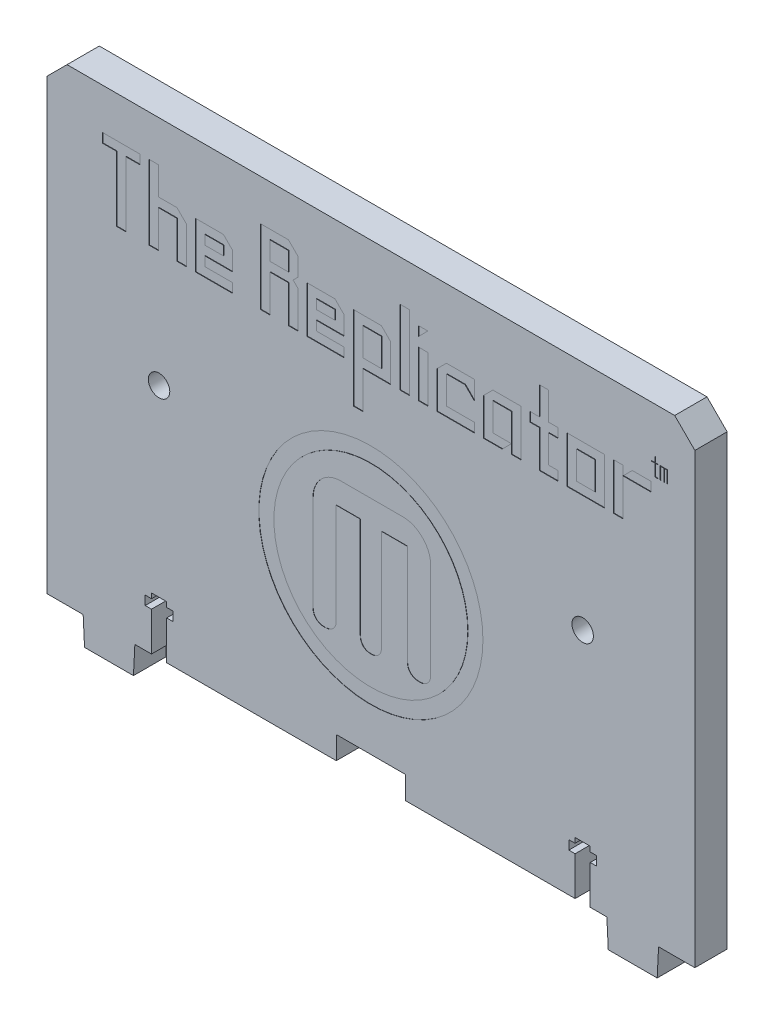
SolidWorks part; units mm, degrees
ref_plane "Front Plane" through (0, 0, 0) normal (0, 0, 1) x (1, 0, 0)
ref_plane "Top Plane" through (0, 0, 0) normal (0, 1, 0) x (1, 0, 0)
ref_plane "Right Plane" through (0, 0, 0) normal (1, 0, 0) x (0, 0, -1)
sketch "Sketch1" plane through (0, 0, 0) normal (0, 0, 1) x (1, 0, 0)
  line L0 (-37.2336, 42.2153) -> (-37.2336, -46.6247)
  line L1 (87.2664, 46.2153) -> (-33.2336, 46.2153)
  line L2 (91.2664, 42.2153) -> (91.2664, -46.6247)
  line L3 (91.2664, -46.6247) -> (84.0664, -46.6247)
  line L4 (-37.2336, -46.6247) -> (-30.0336, -46.6247)
  line L5 (-37.2336, 42.2153) -> (-33.2336, 46.2153)
  line L7 (91.2664, 42.2153) -> (87.2664, 46.2153)
  line L8 (33.8664, -46.6247) -> (33.8664, -42.1247)
  line L9 (-29.7586, -52.1247) -> (-20.0586, -52.1247)
  line L10 (-29.7586, -52.1247) -> (-30.0336, -46.6247)
  line L11 (-20.0586, -52.1247) -> (-19.7836, -46.6247)
  line L13 (20.1664, -46.6247) -> (20.1664, -42.1247)
  line L89 (33.8664, -42.1247) -> (20.1664, -42.1247)
  line L125 (83.7914, -52.1247) -> (84.0664, -46.6247)
  line L126 (-12.2336, -37.1247) -> (-13.4823, -37.1247)
  line L127 (70.5164, -37.1247) -> (71.7664, -37.1247)
  line L128 (66.2664, -38.9247) -> (67.515, -38.9247)
  line L129 (-17.7336, -37.1247) -> (-17.7336, -38.9247)
  line L130 (70.5164, -36.1247) -> (70.5164, -37.1247)
  line L131 (71.7664, -37.1247) -> (71.7664, -38.9247)
  line L132 (-12.2336, -38.9247) -> (-13.4823, -38.9247)
  line L133 (-13.4823, -38.9247) -> (-13.4823, -46.6247)
  line L134 (-16.4836, -37.1247) -> (-17.7336, -37.1247)
  line L135 (66.2664, -37.1247) -> (67.515, -37.1247)
  line L137 (-16.4836, -36.1247) -> (-13.4823, -36.1247)
  line L138 (67.515, -38.9247) -> (67.515, -46.6247)
  line L139 (70.5164, -38.9247) -> (70.5164, -46.6247)
  line L140 (-17.7336, -38.9247) -> (-16.4836, -38.9247)
  line L141 (74.0914, -52.1247) -> (83.7914, -52.1247)
  line L142 (-13.4823, -36.1247) -> (-13.4823, -37.1247)
  line L143 (66.2664, -37.1247) -> (66.2664, -38.9247)
  line L145 (-12.2336, -37.1247) -> (-12.2336, -38.9247)
  line L146 (74.0914, -52.1247) -> (73.8164, -46.6247)
  line L147 (71.7664, -38.9247) -> (70.5164, -38.9247)
  line L148 (-16.4836, -38.9247) -> (-16.4836, -46.6247)
  line L149 (67.515, -36.1247) -> (67.515, -37.1247)
  line L150 (-16.4836, -36.1247) -> (-16.4836, -37.1247)
  line L151 (70.5164, -36.1247) -> (67.515, -36.1247)
  line L152 (-13.4823, -46.6247) -> (20.1664, -46.6247)
  line L153 (-19.7836, -46.6247) -> (-16.4836, -46.6247)
  line L154 (67.515, -46.6247) -> (33.8664, -46.6247)
  line L155 (73.8164, -46.6247) -> (70.5164, -46.6247)
  circle A0 centre (-14.983, 0.2416) radius 2.125
  circle A1 centre (69.0157, 0.2416) radius 2.125
  point P93 (27.0164, -40.5247)
  dimension "D3" = 4.25
extrude "Boss-Extrude1" add sketch "Sketch1" along normal blind 6.4
sketch "Sketch2" plane through (0, 0, 6.4) normal (0, 0, 1) x (1, 0, 0)
  line L0 (34.2644, -22.6031) -> (34.2644, -2.7541)
  line L1 (38.8838, -22.5844) -> (38.8838, -3.7647)
  line L2 (33.248, 1.8654) -> (21.1687, 1.8654)
  line L3 (15.5328, -3.7647) -> (15.5328, -22.5853)
  line L4 (20.1523, -22.6021) -> (20.1523, -2.7541)
  line L5 (20.1523, -2.7541) -> (24.8986, -2.7541)
  line L6 (24.8986, -2.7541) -> (24.8986, -22.6)
  line L7 (29.1434, -22.6) -> (29.1434, -2.7541)
  line L8 (29.1434, -2.7541) -> (34.2644, -2.7541)
  circle A0 centre (27.0136, -11.3473) radius 19.2258
  circle A1 centre (27.0136, -11.3473) radius 22.2258
  spline S0 degree 3 poles (34.2644, -22.6031) (34.2698, -22.7578) (34.2746, -22.913) (34.3187, -23.2193) (34.3612, -23.3661) (34.4711, -23.6521) (34.5384, -23.7926) (34.7062, -24.0461) (34.8074, -24.1612) (35.1475, -24.4744) (35.4177, -24.6332) (35.8518, -24.7756) (36.0034, -24.8079) (36.3084, -24.8442) (36.4619, -24.8505) (36.6155, -24.8569) knots 0 0 0 0 0.125 0.125 0.25 0.25 0.375 0.375 0.5 0.5 0.75 0.75 0.875 0.875 1 1 1 1
  spline S1 degree 3 poles (36.6155, -24.8569) (36.767, -24.8508) (36.9189, -24.8449) (37.2193, -24.8054) (37.3648, -24.7698) (37.6463, -24.6664) (37.7834, -24.5977) (38.0348, -24.4343) (38.1507, -24.3391) (38.4709, -24.0157) (38.6328, -23.7538) (38.7905, -23.3328) (38.8305, -23.1857) (38.8724, -22.8865) (38.8778, -22.7354) (38.8838, -22.5844) knots 0 0 0 0 0.125 0.125 0.25 0.25 0.375 0.375 0.5 0.5 0.75 0.75 0.875 0.875 1 1 1 1
  spline S2 degree 3 poles (38.8838, -3.7647) (38.8784, -3.5782) (38.8731, -3.3917) (38.8439, -3.0196) (38.8194, -2.8353) (38.7173, -2.2917) (38.6129, -1.9393) (38.3325, -1.2544) (38.1569, -0.9229) (37.7384, -0.3186) (37.5005, -0.0366) (36.9765, 0.4911) (36.695, 0.7314) (36.0826, 1.1521) (35.7557, 1.3266) (35.0766, 1.6037) (34.7183, 1.7068) (33.9886, 1.8373) (33.6187, 1.8548) (33.248, 1.8654) knots 0 0 0 0 0.0625 0.0625 0.125 0.125 0.25 0.25 0.375 0.375 0.5 0.5 0.625 0.625 0.75 0.75 0.875 0.875 1 1 1 1
  spline S3 degree 3 poles (21.1687, 1.8654) (20.9822, 1.8601) (20.7957, 1.8549) (20.4237, 1.827) (20.2385, 1.8034) (19.6928, 1.7055) (19.3401, 1.6018) (18.6557, 1.3214) (18.3235, 1.146) (17.7187, 0.7283) (17.4383, 0.4895) (16.9144, -0.0386) (16.6751, -0.322) (16.2529, -0.9341) (16.081, -1.2613) (15.8038, -1.9399) (15.6979, -2.2966) (15.5961, -2.8428) (15.5721, -3.026) (15.5435, -3.3944) (15.5382, -3.5795) (15.5328, -3.7647) knots 0 0 0 0 0.0625 0.0625 0.125 0.125 0.25 0.25 0.375 0.375 0.5 0.5 0.625 0.625 0.75 0.75 0.875 0.875 0.9375 0.9375 1 1 1 1
  spline S4 degree 3 poles (15.5328, -22.5853) (15.5384, -22.7376) (15.5434, -22.8903) (15.5837, -23.1922) (15.6222, -23.3379) (15.7239, -23.622) (15.7863, -23.7622) (15.9426, -24.018) (16.0376, -24.1341) (16.2538, -24.3481) (16.3715, -24.4427) (16.6298, -24.6022) (16.7673, -24.6658) (17.0501, -24.7675) (17.1982, -24.8054) (17.4981, -24.8455) (17.6495, -24.8511) (17.8008, -24.8569) knots 0 0 0 0 0.125 0.125 0.25 0.25 0.375 0.375 0.5 0.5 0.625 0.625 0.75 0.75 0.875 0.875 1 1 1 1
  spline S5 degree 3 poles (17.8008, -24.8569) (17.9545, -24.8505) (18.1083, -24.8442) (18.4136, -24.8079) (18.5655, -24.7755) (19.0001, -24.6327) (19.2709, -24.474) (19.7238, -24.0546) (19.8981, -23.7942) (20.0608, -23.3654) (20.099, -23.2175) (20.1406, -22.9109) (20.1462, -22.7564) (20.1523, -22.6021) knots 0 0 0 0 0.125 0.125 0.25 0.25 0.5 0.5 0.75 0.75 0.875 0.875 1 1 1 1
  spline S6 degree 3 poles (24.8986, -22.6) (24.9126, -22.8932) (24.9308, -23.1889) (25.0582, -23.6064) (25.1172, -23.7426) (25.2586, -23.9976) (25.3397, -24.1184) (25.632, -24.4491) (25.8847, -24.6157) (26.2929, -24.77) (26.4363, -24.8054) (26.7275, -24.8444) (26.8743, -24.8506) (27.0211, -24.8568) knots 0 0 0 0 0.25 0.25 0.375 0.375 0.5 0.5 0.75 0.75 0.875 0.875 1 1 1 1
  spline S7 degree 3 poles (27.0211, -24.8568) (27.168, -24.8506) (27.3149, -24.8445) (27.6066, -24.8052) (27.7486, -24.7699) (28.1575, -24.6161) (28.4047, -24.4464) (28.7964, -24.008) (28.941, -23.7464) (29.0683, -23.329) (29.0965, -23.1838) (29.1296, -22.8929) (29.1365, -22.7465) (29.1434, -22.6) knots 0 0 0 0 0.125 0.125 0.25 0.25 0.5 0.5 0.75 0.75 0.875 0.875 1 1 1 1
extrude "Cut-Extrude1" cut sketch "Sketch2" against normal blind 0.05 contours S6 S7 L7 L8 L0 S0 S1 L1 S2 L2 S3 L3 S4 S5 L4 L5 L6 | A1 A0
sketch "Sketch3" plane through (0, 0, 6.4) normal (0, 0, 1) x (1, 0, 0)
  line L0 (83.4396, 37.2676) -> (83.4396, 36.2011)
  line L1 (83.4396, 33.8131) -> (83.9092, 33.8131)
  line L2 (82.7152, 36.2011) -> (83.3122, 36.2011)
  line L3 (84.3787, 33.6857) -> (84.3787, 36.2011)
  line L4 (84.3787, 36.2011) -> (85.1031, 36.2011)
  line L5 (85.2306, 36.0736) -> (85.2306, 33.6857)
  line L6 (85.1031, 36.2011) -> (85.8275, 36.2011)
  line L7 (85.8275, 36.2011) -> (85.8275, 33.6857)
  line L8 (83.3122, 37.2676) -> (83.4396, 37.2676)
  line L9 (82.7152, 36.2011) -> (82.7152, 36.0736)
  line L10 (83.9092, 36.2011) -> (83.9092, 36.0736)
  line L11 (83.9092, 33.8131) -> (83.9092, 33.6857)
  line L12 (84.3787, 33.6857) -> (84.5061, 33.6857)
  line L13 (85.1031, 33.6857) -> (85.2306, 33.6857)
  line L14 (85.7001, 33.6857) -> (85.8275, 33.6857)
  line L15 (83.4396, 36.0736) -> (83.4396, 33.8131)
  line L17 (83.4396, 36.2011) -> (83.9092, 36.2011)
  line L19 (83.4396, 36.0736) -> (83.9092, 36.0736)
  line L21 (83.3122, 36.0736) -> (83.3122, 33.6857)
  line L23 (53.0578, 23.3473) -> (54.9004, 25.1881)
  line L25 (78.8534, 32.56) -> (77.0109, 30.7177)
  line L159 (5.1518, 38.0876) -> (5.1518, 23.3473)
  line L160 (5.1518, 23.3473) -> (6.9943, 23.3473)
  line L161 (10.6794, 23.3473) -> (12.5219, 23.3473)
  line L162 (12.5219, 36.2451) -> (10.6794, 38.0876)
  line L163 (10.6794, 36.2451) -> (6.9943, 36.2451)
  line L164 (10.6794, 38.0876) -> (5.1518, 38.0876)
  line L165 (23.5772, 30.7175) -> (23.5772, 15.9771)
  line L166 (23.5772, 15.9771) -> (25.4197, 15.9771)
  line L167 (25.4197, 15.9771) -> (25.4197, 23.3473)
  line L168 (25.4197, 23.3473) -> (30.9473, 23.3473)
  line L169 (32.7899, 23.3473) -> (32.7899, 38.0876)
  line L170 (32.7899, 38.0876) -> (34.6324, 38.0876)
  line L171 (34.6324, 38.0876) -> (34.6324, 23.3473)
  line L172 (34.6324, 23.3473) -> (32.7899, 23.3473)
  line L173 (38.3175, 23.3473) -> (36.475, 23.3473)
  line L174 (40.16, 23.3473) -> (47.5302, 23.3473)
  line L175 (47.5302, 23.3473) -> (47.5302, 25.1898)
  line L176 (47.5302, 25.1898) -> (42.0026, 25.1898)
  line L177 (25.4197, 28.8749) -> (25.4197, 25.1898)
  line L178 (25.4197, 25.1898) -> (27.2623, 25.1898)
  line L179 (29.1048, 28.8749) -> (29.1048, 25.1898)
  line L180 (27.2623, 25.1898) -> (29.1048, 25.1898)
  line L181 (56.7429, 30.7175) -> (56.7429, 23.3473)
  line L182 (56.7429, 23.3473) -> (54.9004, 23.3473)
  line L183 (54.9004, 23.3473) -> (54.9004, 25.1881)
  line L185 (53.0578, 23.3473) -> (49.3727, 23.3473)
  line L186 (49.3727, 23.3473) -> (49.3727, 27.0324)
  line L187 (60.428, 23.3473) -> (62.2705, 23.3473)
  line L188 (62.2705, 38.0876) -> (60.428, 38.0876)
  line L189 (65.9556, 30.7175) -> (65.9556, 23.3473)
  line L190 (65.9556, 23.3473) -> (73.3258, 23.3473)
  line L191 (73.3258, 23.3473) -> (73.3258, 30.7175)
  line L192 (67.7982, 25.1898) -> (67.7982, 28.8749)
  line L193 (71.4832, 28.8749) -> (71.4832, 25.1898)
  line L194 (71.4832, 25.1898) -> (67.7982, 25.1898)
  line L195 (49.3727, 28.8749) -> (49.3727, 27.0324)
  line L196 (51.2153, 25.1898) -> (51.2153, 28.8749)
  line L197 (52.2946, 25.1898) -> (51.2153, 25.1898)
  line L198 (30.9473, 23.3473) -> (30.9473, 28.8749)
  line L199 (52.2946, 25.1898) -> (54.9004, 25.1898)
  line L200 (54.9004, 25.1898) -> (54.9004, 28.8749)
  line L201 (10.6794, 36.2451) -> (10.6794, 32.56)
  line L202 (6.9943, 32.56) -> (6.9943, 36.2451)
  line L203 (21.7346, 27.0324) -> (16.207, 27.0324)
  line L204 (16.207, 25.1898) -> (21.7346, 25.1898)
  line L205 (19.8921, 32.56) -> (21.7346, 30.7175)
  line L206 (21.7346, 30.7175) -> (21.7346, 27.0324)
  line L207 (18.0495, 28.8749) -> (19.8921, 28.8749)
  line L208 (19.8921, 28.8749) -> (19.8921, 30.7175)
  line L209 (19.8921, 30.7175) -> (16.207, 30.7175)
  line L210 (19.8921, 23.3473) -> (16.207, 23.3473)
  line L211 (21.7346, 25.1898) -> (21.7346, 23.3473)
  line L212 (21.7346, 23.3473) -> (19.8921, 23.3473)
  line L213 (30.9473, 28.8749) -> (30.9473, 30.7175)
  line L214 (30.9473, 30.7175) -> (29.1048, 32.56)
  line L215 (29.1048, 32.56) -> (23.5772, 32.56)
  line L216 (23.5772, 32.56) -> (23.5772, 30.7175)
  line L217 (25.4197, 28.8749) -> (25.4197, 30.7175)
  line L218 (25.4197, 30.7175) -> (29.1048, 30.7175)
  line L219 (29.1048, 30.7175) -> (29.1048, 28.8749)
  line L220 (36.475, 36.2451) -> (38.3175, 36.2451)
  line L221 (38.3175, 36.2451) -> (36.475, 34.4025)
  line L222 (36.475, 34.4025) -> (36.475, 36.2451)
  line L223 (36.475, 32.56) -> (38.3175, 32.56)
  line L224 (38.3175, 32.56) -> (38.3175, 23.3473)
  line L225 (36.475, 23.3473) -> (36.475, 32.56)
  line L226 (42.0026, 30.7175) -> (45.6877, 30.7175)
  line L227 (45.6877, 30.7175) -> (47.5302, 28.8749)
  line L228 (47.5302, 28.8749) -> (47.5302, 32.56)
  line L229 (42.0026, 25.1898) -> (42.0026, 30.7175)
  line L230 (56.7429, 30.7175) -> (56.7429, 32.56)
  line L231 (56.7429, 32.56) -> (51.2153, 32.56)
  line L232 (51.2153, 32.56) -> (49.3727, 30.7175)
  line L233 (49.3727, 30.7175) -> (49.3727, 28.8749)
  line L234 (51.2153, 28.8749) -> (51.2153, 30.7175)
  line L235 (51.2153, 30.7175) -> (54.9004, 30.7175)
  line L236 (54.9004, 30.7175) -> (54.9004, 28.8749)
  line L237 (60.428, 38.0876) -> (60.428, 32.56)
  line L238 (60.428, 32.56) -> (58.5854, 32.56)
  line L239 (58.5854, 32.56) -> (58.5854, 30.7175)
  line L240 (58.5854, 30.7175) -> (60.428, 30.7175)
  line L241 (60.428, 30.7175) -> (60.428, 23.3473)
  line L242 (62.2705, 23.3473) -> (64.1131, 23.3473)
  line L243 (64.1131, 23.3473) -> (64.1131, 25.1898)
  line L244 (64.1131, 25.1898) -> (62.2705, 25.1898)
  line L245 (62.2705, 25.1898) -> (62.2705, 30.7175)
  line L246 (62.2705, 30.7175) -> (64.1131, 30.7175)
  line L247 (64.1131, 30.7175) -> (64.1131, 32.56)
  line L248 (64.1131, 32.56) -> (62.2705, 32.56)
  line L249 (62.2705, 32.56) -> (62.2705, 38.0876)
  line L250 (65.9556, 30.7175) -> (65.9556, 32.56)
  line L251 (65.9556, 32.56) -> (73.3258, 32.56)
  line L252 (73.3258, 32.56) -> (73.3258, 30.7175)
  line L253 (71.4832, 28.8749) -> (71.4832, 30.7175)
  line L254 (67.7982, 28.8749) -> (67.7982, 30.7175)
  line L255 (71.4832, 30.7175) -> (67.7982, 30.7175)
  line L256 (75.1683, 32.56) -> (77.0109, 32.56)
  line L257 (77.0109, 32.56) -> (77.0109, 30.7177)
  line L259 (78.8534, 32.56) -> (82.5385, 32.56)
  line L260 (82.5385, 32.56) -> (82.5385, 30.7175)
  line L261 (82.5385, 30.7175) -> (77.0109, 30.7175)
  line L262 (77.0109, 23.3473) -> (75.1683, 23.3473)
  line L263 (77.0109, 30.7175) -> (77.0109, 23.3473)
  line L264 (75.1683, 23.3473) -> (75.1683, 32.56)
  line L265 (40.16, 30.7175) -> (40.16, 23.3473)
  line L266 (47.5302, 32.56) -> (42.0026, 32.56)
  line L267 (42.0026, 32.56) -> (40.16, 30.7175)
  line L268 (18.0495, 28.8749) -> (16.207, 28.8749)
  line L269 (14.3645, 25.1898) -> (14.3645, 23.3473)
  line L270 (14.3645, 23.3473) -> (16.207, 23.3473)
  line L271 (14.3645, 32.56) -> (19.8921, 32.56)
  line L272 (14.3645, 25.1898) -> (14.3645, 32.56)
  line L273 (16.207, 28.8749) -> (16.207, 30.7175)
  line L274 (16.207, 25.1898) -> (16.207, 27.0324)
  line L275 (6.9943, 32.56) -> (10.6794, 32.56)
  line L276 (10.6794, 30.7175) -> (6.9943, 30.7175)
  line L277 (6.9943, 23.3473) -> (6.9943, 30.7175)
  line L278 (10.6794, 30.7175) -> (10.6794, 23.3473)
  line L279 (12.5219, 32.56) -> (11.6007, 31.6387)
  line L280 (11.6007, 31.6387) -> (12.5219, 30.7175)
  line L281 (12.5219, 23.3473) -> (12.5219, 30.7175)
  line L282 (12.5219, 36.2451) -> (12.5219, 32.56)
  line L283 (-18.8013, 38.0876) -> (-18.8013, 36.2451)
  line L284 (-16.9587, 38.0876) -> (-16.9587, 23.3473)
  line L285 (-16.9587, 23.3473) -> (-15.1162, 23.3473)
  line L286 (-11.4311, 28.8749) -> (-11.4311, 23.3473)
  line L287 (-11.4311, 23.3473) -> (-9.5886, 23.3473)
  line L288 (-15.1162, 38.0876) -> (-16.9587, 38.0876)
  line L289 (-9.5886, 23.3473) -> (-9.5886, 28.8749)
  line L290 (-0.3759, 27.0324) -> (-5.9035, 27.0324)
  line L291 (-5.9035, 27.0324) -> (-5.9035, 25.1898)
  line L292 (-5.9035, 25.1898) -> (-0.3759, 25.1898)
  line L293 (-15.1162, 32.56) -> (-11.4311, 32.56)
  line L294 (-11.4311, 32.56) -> (-9.5886, 30.7175)
  line L295 (-9.5886, 30.7175) -> (-9.5886, 28.8749)
  line L296 (-11.4311, 28.8749) -> (-11.4311, 30.7175)
  line L297 (-11.4311, 30.7175) -> (-15.1162, 30.7175)
  line L298 (-15.1162, 32.56) -> (-15.1162, 38.0876)
  line L299 (-15.1162, 23.3473) -> (-15.1162, 30.7175)
  line L300 (-2.2184, 32.56) -> (-0.3759, 30.7175)
  line L301 (-0.3759, 30.7175) -> (-0.3759, 27.0324)
  line L302 (-2.2184, 28.8749) -> (-2.2184, 30.7175)
  line L303 (-2.2184, 30.7175) -> (-5.9035, 30.7175)
  line L304 (-5.9035, 30.7175) -> (-5.9035, 28.8749)
  line L305 (-0.3759, 25.1898) -> (-0.3759, 23.3473)
  line L306 (-5.9035, 28.8749) -> (-2.2184, 28.8749)
  line L307 (-7.746, 32.56) -> (-2.2184, 32.56)
  line L308 (-0.3759, 23.3473) -> (-7.746, 23.3473)
  line L309 (-7.746, 23.3473) -> (-7.746, 32.56)
  line L310 (-23.4076, 23.3473) -> (-23.4076, 36.2451)
  line L311 (-21.5651, 36.2451) -> (-21.5651, 23.3473)
  line L312 (-21.5651, 23.3473) -> (-23.4076, 23.3473)
  line L313 (-18.8013, 36.2451) -> (-21.5651, 36.2451)
  line L314 (-26.1714, 38.0876) -> (-26.1714, 36.2451)
  line L315 (-26.1714, 38.0876) -> (-18.8013, 38.0876)
  line L316 (-23.4076, 36.2451) -> (-26.1714, 36.2451)
  line L317 (83.3122, 37.2676) -> (83.3122, 36.2011)
  line L318 (83.3122, 33.6857) -> (83.9092, 33.6857)
  line L319 (82.7152, 36.0736) -> (83.3122, 36.0736)
  line L320 (84.5061, 33.6857) -> (84.5061, 36.0736)
  line L321 (84.5061, 36.0736) -> (85.1031, 36.0736)
  line L322 (85.1031, 36.0736) -> (85.1031, 33.6857)
  line L323 (85.2306, 36.0736) -> (85.7001, 36.0736)
  line L324 (85.7001, 36.0736) -> (85.7001, 33.6857)
  point P0 (74.0759, -15.738)
  point P1 (74.0759, -17.0933)
  point P3 (73.7917, -16.1564)
  point P4 (74.2601, -16.1564)
  point P315 (74.0259, -15.738)
  point P316 (74.0259, -17.1433)
  point P318 (73.7917, -16.2064)
  point P319 (74.2601, -16.2064)
  point P322 (74.7286, -16.2064)
  point P324 (74.9628, -16.2064)
extrude "Cut-Extrude5" cut sketch "Sketch3" against normal blind 0.1
